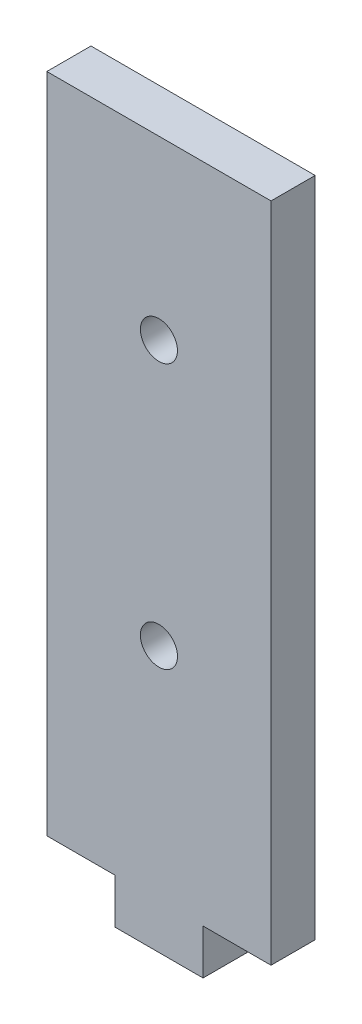
SolidWorks part; units mm, degrees
ref_plane "Front Plane" through (0, 0, 0) normal (0, 0, 1) x (1, 0, 0)
ref_plane "Top Plane" through (0, 0, 0) normal (0, 1, 0) x (1, 0, 0)
ref_plane "Right Plane" through (0, 0, 0) normal (1, 0, 0) x (0, 0, -1)
sketch "Sketch1" plane through (0, 0, 0) normal (0, 0, 1) x (1, 0, 0)
  line L1 (-12.7, 37.5) -> (12.7, 37.5)
  line L2 (-12.7, 37.5) -> (-12.7, -37.5)
  line L3 (-12.7, -37.5) -> (12.7, -37.5)
  line L4 (12.7, 37.5) -> (12.7, -37.5)
  line L5 (-12.7, 37.5) -> (12.7, -37.5) construction
  line L6 (-12.7, -37.5) -> (12.7, 37.5) construction
  circle A0 centre (0, -12.5) radius 2.1
  circle A1 centre (0, 17.5) radius 2.1
  point P0 (0, 0)
  dimension "D3" = 4.2
  dimension "D4" = 4.2
  dimension "D1" = 25.4
  dimension "D2" = 75
  dimension "D5" = 30
  dimension "D6" = 25
  dimension "D7" = 12.7
extrude "Boss-Extrude1" add sketch "Sketch1" along normal blind 5
sketch "Sketch2" plane through (0, 0, 5) normal (0, 0, 1) x (1, 0, 0)
  line L0 (-12.7, -37.5) -> (12.7, -37.5) construction
  line L1 (-5, -32.4) -> (5, -32.4)
  line L2 (-5, -32.4) -> (-5, -42.6)
  line L3 (-5, -42.6) -> (5, -42.6)
  line L4 (5, -32.4) -> (5, -42.6)
  line L5 (-5, -32.4) -> (5, -42.6) construction
  line L6 (-5, -42.6) -> (5, -32.4) construction
  point P0 (0, -37.5)
  dimension "D1" = 10
  dimension "D2" = 10.2
extrude "Boss-Extrude2" add sketch "Sketch2" against normal blind 5
